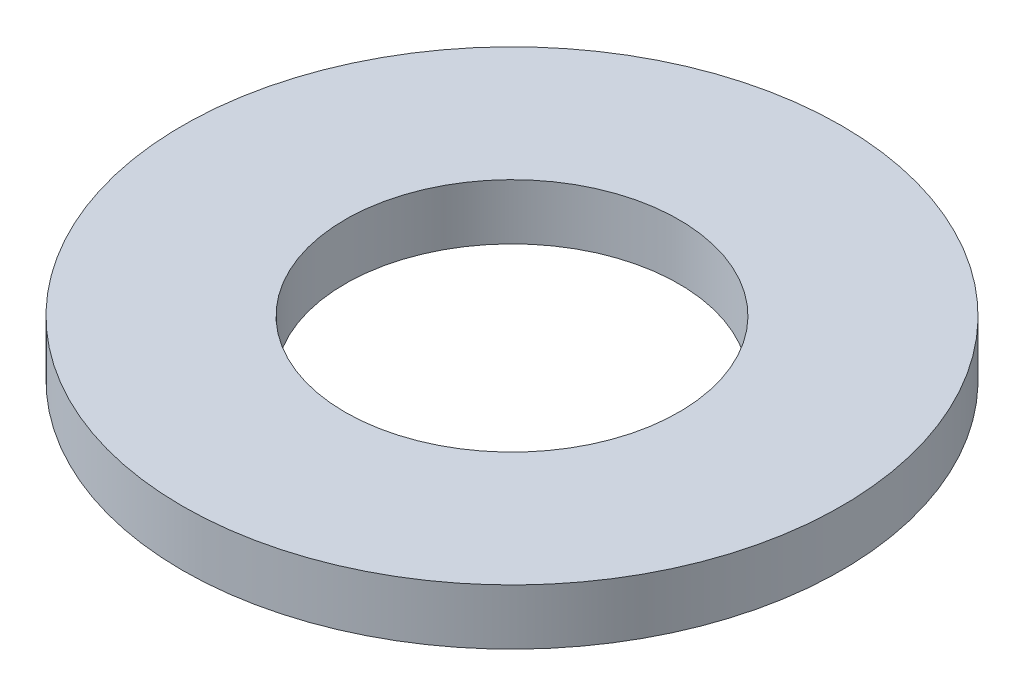
SolidWorks part; units mm, degrees
ref_plane "Front Plane" through (0, 0, 0) normal (0, 0, 1) x (1, 0, 0)
ref_plane "Top Plane" through (0, 0, 0) normal (0, 1, 0) x (1, 0, 0)
ref_plane "Right Plane" through (0, 0, 0) normal (1, 0, 0) x (0, 0, -1)
sketch "Sketch1" plane through (0, 0, 0) normal (0, 1, 0) x (1, 0, 0)
  circle A0 centre (0, 0) radius 11.85
  circle A1 centre (0, 0) radius 6
  dimension "D1" = 23.7
  dimension "D2" = 12
extrude "Boss-Extrude1" add sketch "Sketch1" along normal blind 2
